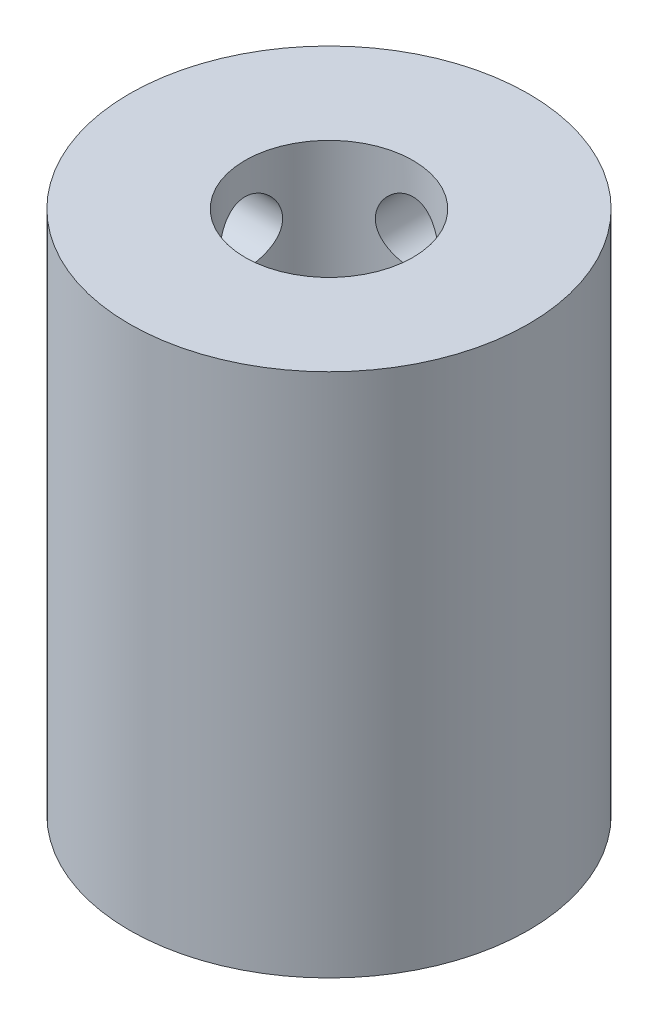
SolidWorks part; units mm, degrees
ref_plane "前视基准面" through (0, 0, 0) normal (0, 0, 1) x (1, 0, 0)
ref_plane "上视基准面" through (0, 0, 0) normal (0, 1, 0) x (1, 0, 0)
ref_plane "右视基准面" through (0, 0, 0) normal (1, 0, 0) x (0, 0, -1)
sketch "草图1" plane through (0, 0, 0) normal (0, 1, 0) x (1, 0, 0)
  circle A0 centre (0, 0) radius 9.5
  circle A1 centre (0, 0) radius 3
  dimension "D1" = 19
  dimension "D2" = 6
extrude "凸台-拉伸1" add sketch "草图1" along normal blind 25
sketch "草图2" plane through (0, 25, 0) normal (0, 1, 0) x (1, 0, 0)
  circle A0 centre (0, 0) radius 4
  dimension "D1" = 8
extrude "切除-拉伸1" cut sketch "草图2" against normal blind 10
sketch "草图3" plane through (0, 0, 0) normal (1, 0, 0) x (0, 0, -1)
  line L0 (0, 33.6391) -> (0, -8.8097) construction
  line L1 (9.5, 25) -> (-9.5, 25) construction
  circle A0 centre (0, 3) radius 1.5
  circle A1 centre (0, 22) radius 1.5
  dimension "D1" = 3
  dimension "D4" = 3
  dimension "D2" = 3
  dimension "D3" = 3
extrude "切除-拉伸2" cut sketch "草图3" against normal blind 10
sketch "草图4" plane through (0, 0, 0) normal (0, 0, 1) x (1, 0, 0)
  line L0 (0, 39.814) -> (0, -14.3868) construction
  line L2 (9.5, 25) -> (-9.5, 25) construction
  line L3 (-9.5, 0) -> (9.5, 0) construction
  circle A0 centre (0, 3) radius 1.5
  circle A1 centre (0, 22) radius 1.5
  dimension "D3" = 3
  dimension "D4" = 3
  dimension "D1" = 3
  dimension "D2" = 3
extrude "切除-拉伸3" cut sketch "草图4" against normal blind 10
